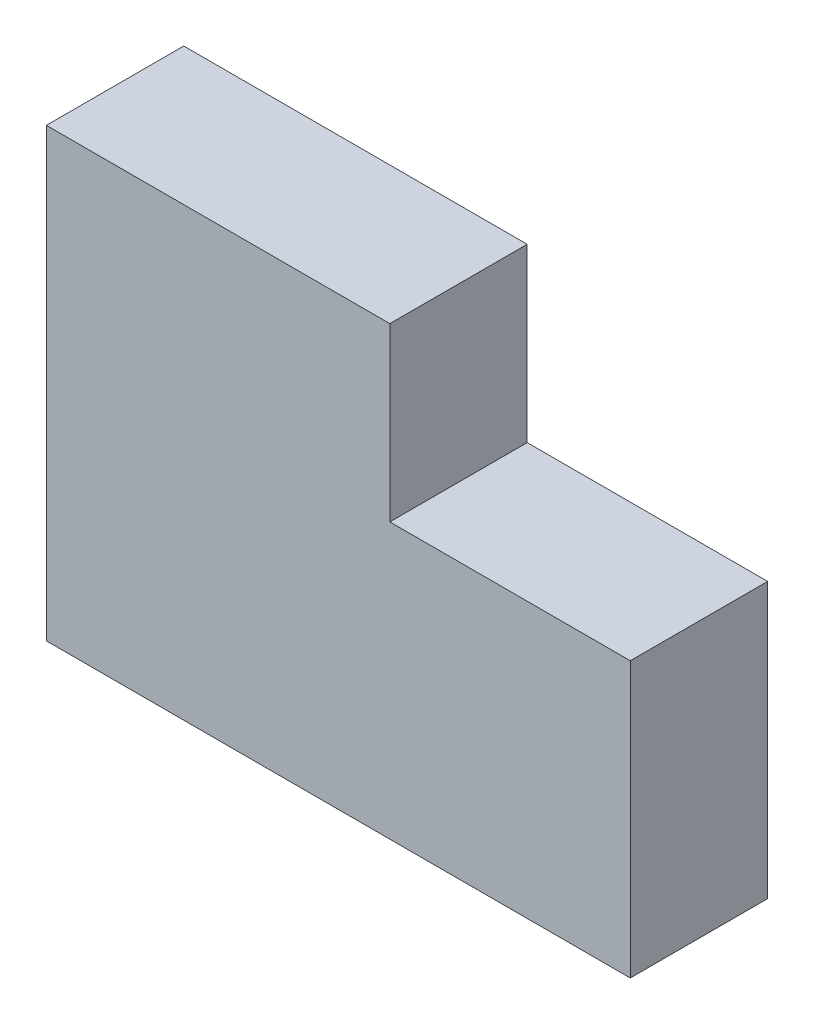
SolidWorks part; units mm, degrees
ref_plane "Front Plane" through (0, 0, 0) normal (0, 0, 1) x (1, 0, 0)
ref_plane "Top Plane" through (0, 0, 0) normal (0, 1, 0) x (1, 0, 0)
ref_plane "Right Plane" through (0, 0, 0) normal (1, 0, 0) x (0, 0, -1)
sketch "Croquis1" plane through (0, 0, 0) normal (0, 0, 1) x (1, 0, 0)
  line L0 (0, 0) -> (85, 0)
  line L1 (85, 0) -> (85, 40)
  line L2 (85, 40) -> (50, 40)
  line L3 (50, 40) -> (50, 65)
  line L4 (50, 65) -> (0, 65)
  line L5 (0, 65) -> (0, 0)
  dimension "D1" = 85
  dimension "D2" = 40
  dimension "D3" = 65
  dimension "D4" = 50
extrude "Saliente-Extruir1" add sketch "Croquis1" along normal blind 20 contours L5 L0 L1 L2 L3 L4
